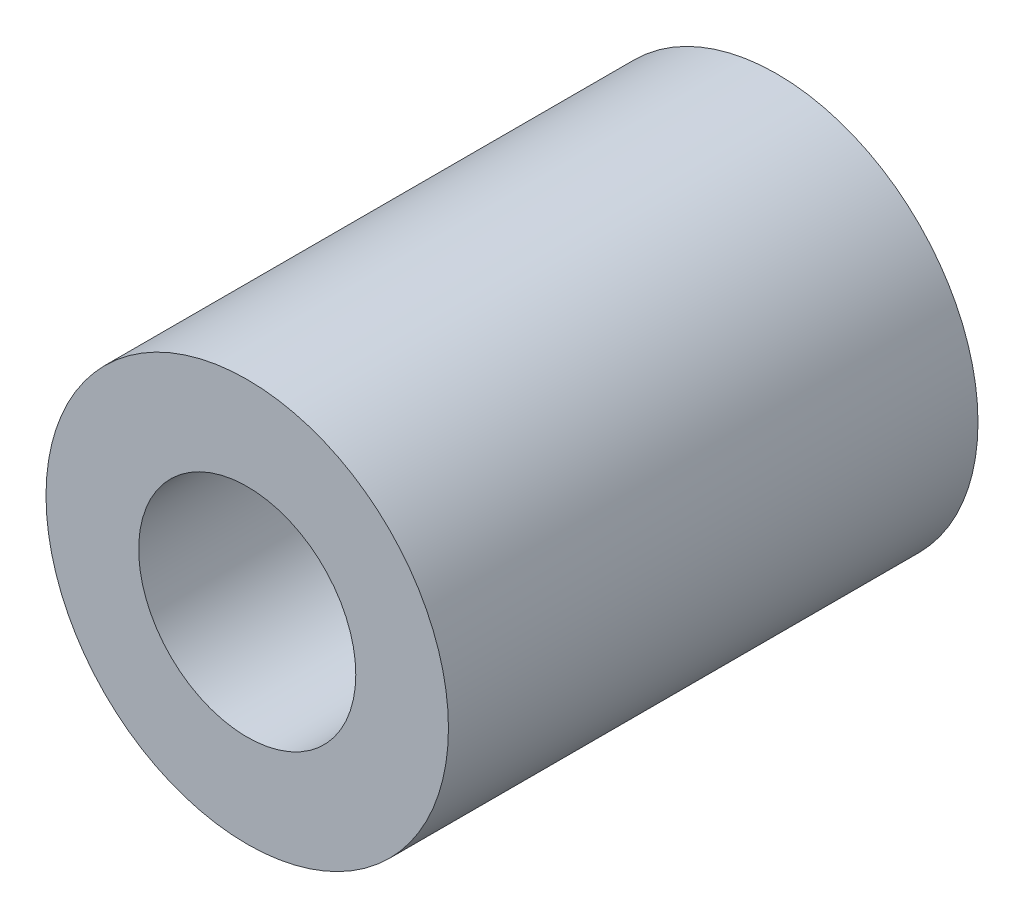
SolidWorks part; units mm, degrees
ref_plane "Plan de face" through (0, 0, 0) normal (0, 0, 1) x (1, 0, 0)
ref_plane "Plan de dessus" through (0, 0, 0) normal (0, 1, 0) x (1, 0, 0)
ref_plane "Plan de droite" through (0, 0, 0) normal (1, 0, 0) x (0, 0, -1)
sketch "Esquisse1" plane through (0, 0, 0) normal (0, 0, 1) x (1, 0, 0)
  circle A0 centre (0, 0) radius 9.5
  dimension "D1" = 19
extrude "Boss.-Extru.1" add sketch "Esquisse1" along normal blind 25
sketch "Esquisse2" plane through (0, 0, 25) normal (0, 0, 1) x (1, 0, 0)
  circle A0 centre (0, 0) radius 5.125
  dimension "D1" = 10.25
extrude "Enlèv. mat.-Extru.1" cut sketch "Esquisse2" against normal blind 18
sketch "Esquisse3" plane through (0, 0, 0) normal (0, 0, -1) x (-1, 0, 0)
  circle A0 centre (0, 0) radius 3.125
  dimension "D1" = 6.25
extrude "Enlèv. mat.-Extru.2" cut sketch "Esquisse3" against normal blind 18
